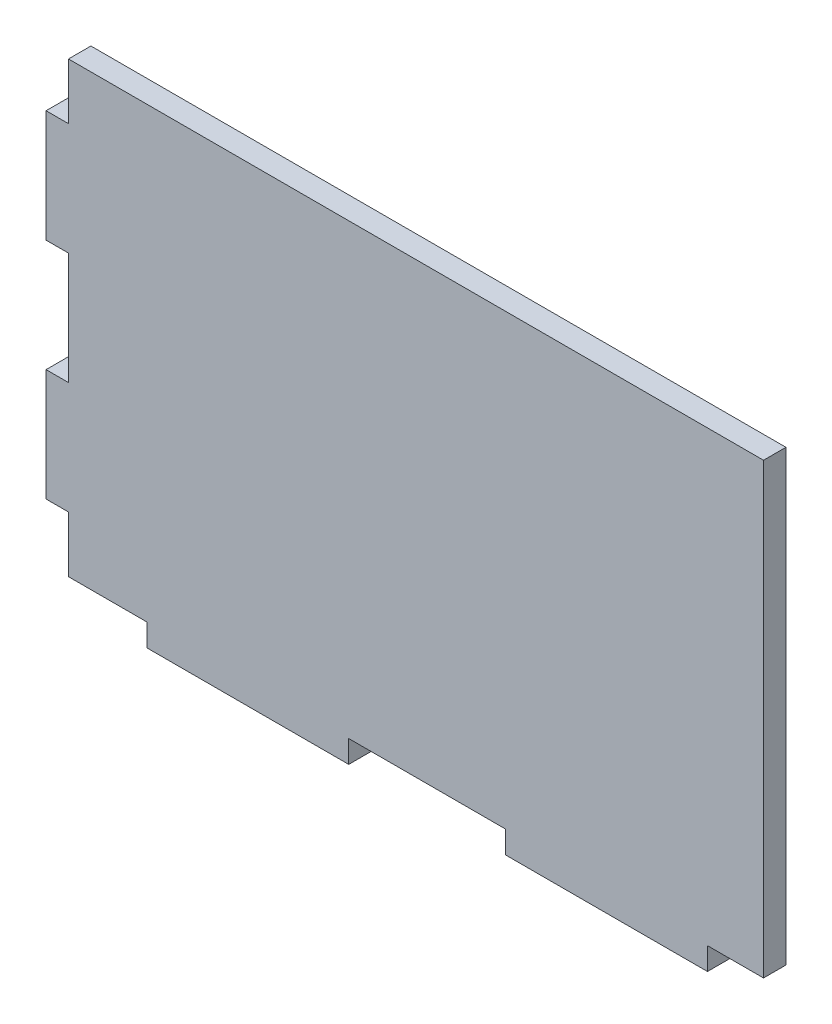
SolidWorks part; units mm, degrees
other "Marca1"
sketch "Croquis4" plane through (160, -5, 5) normal (0.0365, -0.3193, 0.947) x (0.9993, 0.0222, -0.031)
ref_plane "Alzado" through (0, 0, 0) normal (0, 0, 1) x (1, 0, 0)
ref_plane "Planta" through (0, 0, 0) normal (0, 1, 0) x (1, 0, 0)
ref_plane "Vista lateral" through (0, 0, 0) normal (1, 0, 0) x (0, 0, -1)
sketch "Croquis1" plane through (0, 0, 0) normal (0, 0, 1) x (1, 0, 0)
  line L0 (80, 0) -> (80, -48.4233) construction
  line L1 (0, 0) -> (17.5, 0)
  line L2 (0, 0) -> (0, 100)
  line L3 (0, 100) -> (155, 100)
  line L4 (155, 0) -> (155, 100)
  line L5 (142.5, -5) -> (97.5, -5)
  line L7 (17.5, 0) -> (17.5, -5)
  line L8 (17.5, -5) -> (62.5, -5)
  line L9 (62.5, 0) -> (62.5, -5)
  line L10 (97.5, 0) -> (97.5, -5)
  line L12 (142.5, 0) -> (142.5, -5)
  line L13 (62.5, 0) -> (97.5, 0)
  line L14 (142.5, 0) -> (155, 0)
  line L15 (0, 100) -> (0, 87.5) construction
  line L16 (0, 50) -> (-28.3674, 50) construction
  line L17 (0, 87.5) -> (5, 87.5)
  line L18 (0, 87.5) -> (0, 62.5)
  line L19 (0, 62.5) -> (5, 62.5)
  line L20 (5, 87.5) -> (5, 62.5)
  line L21 (0, 37.5) -> (5, 37.5)
  line L22 (5, 12.5) -> (5, 37.5)
  line L23 (0, 12.5) -> (5, 12.5)
  line L24 (0, 12.5) -> (0, 37.5)
  dimension "D1" = 155
  dimension "D2" = 100
  dimension "D3" = 45
  dimension "D4" = 17.5
  dimension "D5" = 5
  dimension "D6" = 25
  dimension "D7" = 12.5
  dimension "D8" = 5
  dimension "D9" = 17.5
extrude "Saliente-Extruir1" add sketch "Croquis1" along normal blind 5 contours L23 L2 L1 L7 L8 L9 L13 L10 L5 L12 L14 L4 L3 L17 L20 L19 L21 L22 | L2 L23 L22 L21 | L20 L17 L2 L19
sketch "Croquis3" plane through (0, 0, 5) normal (0, 0, 1) x (1, 0, 0)
  line L0 (0, 0) -> (0, 100) construction
  line L1 (0, 87.5) -> (-5, 87.5)
  line L2 (0, 87.5) -> (0, 62.5)
  line L3 (0, 62.5) -> (-5, 62.5)
  line L4 (-5, 87.5) -> (-5, 62.5)
  line L5 (0, 50) -> (-36.6844, 50) construction
  line L6 (0, 62.5) -> (5, 62.5)
  line L7 (0, 62.5) -> (0, 37.5)
  line L8 (0, 37.5) -> (5, 37.5)
  line L9 (5, 62.5) -> (5, 37.5)
  line L10 (0, 37.5) -> (-5, 37.5)
  line L11 (-5, 12.5) -> (-5, 37.5)
  line L12 (0, 12.5) -> (-5, 12.5)
  line L13 (0, 12.5) -> (0, 37.5)
  line M11 (0, 100) -> (0, 0)
  dimension "D1" = 25
  dimension "D2" = 12.5
  dimension "D3" = 5
  dimension "D4" = 25
  dimension "D5" = 5
extrude "Saliente-Extruir2" add sketch "Croquis3" against normal blind 5 contours L12 L10 L11 M11 | L1 L4 L3 M11
